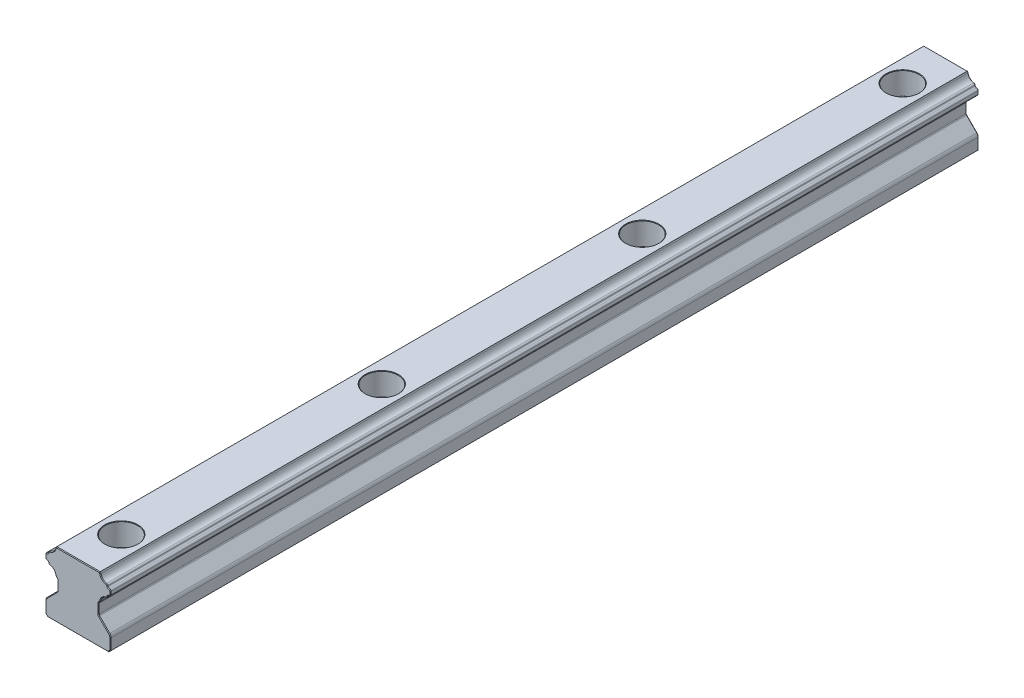
SolidWorks part; units mm, degrees
material "Plain Carbon Steel"
ref_plane "Front Plane" through (0, 0, 0) normal (0, 0, 1) x (1, 0, 0)
ref_plane "Top Plane" through (0, 0, 0) normal (0, 1, 0) x (1, 0, 0)
ref_plane "Right Plane" through (0, 0, 0) normal (1, 0, 0) x (0, 0, -1)
sketch "Rail Profile" plane through (0, 0, 0) normal (0, 0, 1) x (1, 0, 0)
  line L47 (0, 0) -> (0, 20) construction
  line L48 (-7, 0) -> (7, 0)
  line L49 (7, 0) -> (7.5, 0.5)
  line L50 (7.5, 0.5) -> (7.5, 3.0858)
  line L58 (7.2071, 3.7929) -> (4.8672, 6.1328)
  line L59 (4.75, 6.4157) -> (4.75, 8.5843)
  line L60 (4.8672, 8.8672) -> (5.063, 9.063)
  line L61 (7.5, 11.6657) -> (7.5, 12.3343)
  line L62 (-7, 0) -> (-7.5, 0.5)
  line L63 (5, 15) -> (-5, 15)
  line L64 (6.75, 9) -> (6.75, 15) construction
  line L65 (5.063, 14.937) -> (5, 15)
  line L66 (-7.5, 0.5) -> (-7.5, 3.0858)
  line L67 (6.75, 15) -> (3.75, 12) construction
  line L68 (3.75, 12) -> (6.75, 9) construction
  line L69 (7.1, 12.3343) -> (7.1, 11.6657) construction
  line L70 (6.4042, 13.0301) -> (6.4042, 10.9699) construction
  line L71 (-7.2071, 3.7929) -> (-4.8672, 6.1328)
  line L72 (-4.75, 6.4157) -> (-4.75, 8.5843)
  line L73 (-4.8672, 8.8672) -> (-5.063, 9.063)
  line L74 (5, 15) -> (8, 12) construction
  line L75 (4.8672, 8.8672) -> (8, 12) construction
  line L76 (-7.5, 11.6657) -> (-7.5, 12.3343)
  line L77 (-5.063, 14.937) -> (-5, 15)
  arc A4 (6.4734, 13.4241) -> (5.1741, 14.7234) centre (6.75, 15) cw
  arc A6 (5.1741, 9.2766) -> (6.4734, 10.5759) centre (6.75, 9) cw
  arc A7 (7.2071, 3.7929) -> (7.5, 3.0858) centre (6.5, 3.0858) cw
  arc A8 (5.063, 14.937) -> (5.1741, 14.7234) centre (4.7801, 14.6542) cw
  arc A9 (6.4734, 13.4241) -> (6.8012, 13.0792) centre (6.4042, 13.0301) cw
  arc A10 (7.1491, 12.7313) -> (7.5, 12.3343) centre (7.1, 12.3343) cw
  arc A11 (7.5, 11.6657) -> (7.1491, 11.2687) centre (7.1, 11.6657) cw
  arc A12 (6.8012, 10.9208) -> (6.4734, 10.5759) centre (6.4042, 10.9699) cw
  arc A13 (5.1741, 9.2766) -> (5.063, 9.063) centre (4.7801, 9.3458) cw
  arc A14 (4.8672, 8.8672) -> (4.75, 8.5843) centre (5.15, 8.5843) ccw
  arc A15 (4.75, 6.4157) -> (4.8672, 6.1328) centre (5.15, 6.4157) ccw
  arc A16 (6.8012, 13.0792) -> (7.1491, 12.7313) centre (7.1981, 13.1283) ccw
  arc A17 (7.1491, 11.2687) -> (6.8012, 10.9208) centre (7.1981, 10.8717) ccw
  arc A18 (-7.2071, 3.7929) -> (-7.5, 3.0858) centre (-6.5, 3.0858) ccw
  arc A19 (-4.75, 6.4157) -> (-4.8672, 6.1328) centre (-5.15, 6.4157) cw
  arc A20 (-4.8672, 8.8672) -> (-4.75, 8.5843) centre (-5.15, 8.5843) cw
  arc A21 (-5.1741, 9.2766) -> (-5.063, 9.063) centre (-4.7801, 9.3458) ccw
  arc A22 (-5.1741, 9.2766) -> (-6.4734, 10.5759) centre (-6.75, 9) ccw
  arc A23 (-6.8012, 10.9208) -> (-6.4734, 10.5759) centre (-6.4042, 10.9699) ccw
  arc A24 (-7.1491, 11.2687) -> (-6.8012, 10.9208) centre (-7.1981, 10.8717) cw
  arc A25 (-7.5, 11.6657) -> (-7.1491, 11.2687) centre (-7.1, 11.6657) ccw
  arc A26 (-7.1491, 12.7313) -> (-7.5, 12.3343) centre (-7.1, 12.3343) ccw
  arc A27 (-6.8012, 13.0792) -> (-7.1491, 12.7313) centre (-7.1981, 13.1283) cw
  arc A28 (-6.4734, 13.4241) -> (-6.8012, 13.0792) centre (-6.4042, 13.0301) ccw
  arc A29 (-6.4734, 13.4241) -> (-5.1741, 14.7234) centre (-6.75, 15) ccw
  arc A30 (-5.063, 14.937) -> (-5.1741, 14.7234) centre (-4.7801, 14.6542) ccw
  point P2 (4.75, 7.5)
  point P12 (7.5, 12)
  point P19 (6.75, 12)
  point P25 (5.1578, 14.8422)
  point P50 (8, 12)
  point P78 (0, 15)
  dimension "Rb" = 1.6
  dimension "Rf1" = 1
  dimension "Rf2" = 0.4
  dimension "WR" = 15
  dimension "Wi" = 9.5
  dimension "Wt" = 5
  dimension "Ac" = 135
  dimension "HR" = 15
  dimension "Hm" = 7.5
  dimension "Hb" = 12
  dimension "Hc" = 0.5
  dimension "Wb" = 7.5
extrude "Body" add sketch "Rail Profile" against normal blind 200
chamfer "Aesthetic Chamfer" distance 0.15 angle 45 84 edges at (-5.0315, 14.9685, 0) (-5.135, 14.8388, 0) (-5.6186, 13.8686, 0) (-6.6941, 13.3057, 0) (-6.9153, 12.8454, 0) (-7.3997, 12.5992, 0) (-7.5, 12, 0) (-7.3997, 11.4008, 0) (-6.9153, 11.1546, 0) (-6.6941, 10.6943, 0) (-5.6186, 10.1314, 0) (-5.135, 9.1612, 0) (-4.9651, 8.9651, 0) (-4.7804, 8.7374, 0) (-4.75, 7.5, 0) (-4.7804, 6.2626, 0) (-6.0371, 4.9629, 0) (-7.4239, 3.4685, 0) (-7.5, 1.7929, 0) (-7.25, 0.25, 0) (0, 0, 0) (7.25, 0.25, 0) (5.0315, 14.9685, 0) (5.135, 14.8388, 0) (5.6186, 13.8686, 0) (6.6941, 13.3057, 0) (6.9153, 12.8454, 0) (7.3997, 12.5992, 0) (7.5, 12, 0) (7.3997, 11.4008, 0) (6.9153, 11.1546, 0) (6.6941, 10.6943, 0) (5.6186, 10.1314, 0) (5.135, 9.1612, 0) (4.9651, 8.9651, 0) (4.7804, 8.7374, 0) (7.5, 1.7929, 0) (4.75, 7.5, 0) (7.4239, 3.4685, 0) (4.7804, 6.2626, 0) (6.0371, 4.9629, 0) (0, 15, 0) (5.0315, 14.9685, -200) (5.135, 14.8388, -200) (5.6186, 13.8686, -200) (6.6941, 13.3057, -200) (6.9153, 12.8454, -200) (7.3997, 12.5992, -200) (7.5, 12, -200) (7.3997, 11.4008, -200) (6.9153, 11.1546, -200) (6.6941, 10.6943, -200) (5.6186, 10.1314, -200) (5.135, 9.1612, -200) (4.9651, 8.9651, -200) (4.7804, 8.7374, -200) (4.75, 7.5, -200) (4.7804, 6.2626, -200) (6.0371, 4.9629, -200) (7.4239, 3.4685, -200) (7.5, 1.7929, -200) (7.25, 0.25, -200) (0, 0, -200) (-7.25, 0.25, -200) (-5.0315, 14.9685, -200) (-5.135, 14.8388, -200) (-5.6186, 13.8686, -200) (-6.6941, 13.3057, -200) (-6.9153, 12.8454, -200) (-7.3997, 12.5992, -200) (-7.5, 12, -200) (-7.3997, 11.4008, -200) (-6.9153, 11.1546, -200) (-6.6941, 10.6943, -200) (-5.6186, 10.1314, -200) (-7.5, 1.7929, -200) (-5.135, 9.1612, -200) (-7.4239, 3.4685, -200) (-4.9651, 8.9651, -200) (-6.0371, 4.9629, -200) (-4.7804, 8.7374, -200) (-4.7804, 6.2626, -200) (-4.75, 7.5, -200) (0, 15, -200)
hole_wizard "Mounting Hole" positions "3DSketch1" profile "Sketch1" counterbore size "M4" standard "ISO" end condition through all
sketch3d "3DSketch1"
  point P0 (0, 15, -10)
  dimension "D1" = 7.5
  dimension "E1" = 10
sketch "Sketch1" plane through (0, 15, -10) normal (1, 0, 0) x (0, 0, 1)
  line L0 (0, 0) -> (0, 15)
  line L1 (2.25, 14.9) -> (2.35, 15)
  line L2 (2.25, 14.9) -> (2.25, 5.4)
  line L3 (2.25, 5.4) -> (2.35, 5.3)
  line L4 (2.35, 5.3) -> (3.75, 5.3)
  line L5 (3.75, 5.3) -> (3.75, 0.1)
  line L6 (3.75, 0.1) -> (3.85, 0)
  line L7 (3.85, 0) -> (0, 0)
  line L8 (-3.75, 0.1) -> (-3.85, 0) construction
  line L9 (-2.25, 5.4) -> (-2.35, 5.3) construction
  line L11 (0, -6.35) -> (0, 107.95) construction
  line L12 (2.35, 15) -> (0, 15)
  line L13 (-2.25, 14.9) -> (-2.35, 15) construction
  dimension "Thru Hole Dia." = 4.5
  dimension "Thru Hole Depth" = 15
  dimension "C'Bore Dia." = 7.5
  dimension "C'Bore Depth" = 5.3
  dimension "Near C'Sink Dia." = 7.7
  dimension "Near C'Sink Angle" = 90
  dimension "Mid C'Sink Dia." = 4.7
  dimension "Mid C'Sink Angle" = 90
  dimension "Far C'Sink Dia." = 4.7
  dimension "Far C'Sink Angle" = 90
fillet "Production Fillet" radius 0.1 1 edges at (0, 9.7, -6.25)
pattern_linear "Mounting Holes Pattern" count 4 spacing 60 along (0, 0, -1) of "Mounting Hole", "Production Fillet"
equation "\"Wt@Rail Profile\"= \"WR@Rail Profile\" / 3'Top Side Half Width"
equation "\"Hm@Rail Profile\"= \"HR@Rail Profile\" / 2'Recirculation Avoidance Height"
equation "\"Hb@Rail Profile\"= 0.8 * \"HR@Rail Profile\"'Pivot Height"
equation "\"Hc@Rail Profile\"= \"WR@Rail Profile\" / 30'Chamfer Width"
equation "\"Wb@Rail Profile\"= \"WR@Rail Profile\" / 2'Ball Center Cross Width"
equation "\"D1@3DSketch1\"= \"WR@Rail Profile\" / 2'Hole Center Position"
